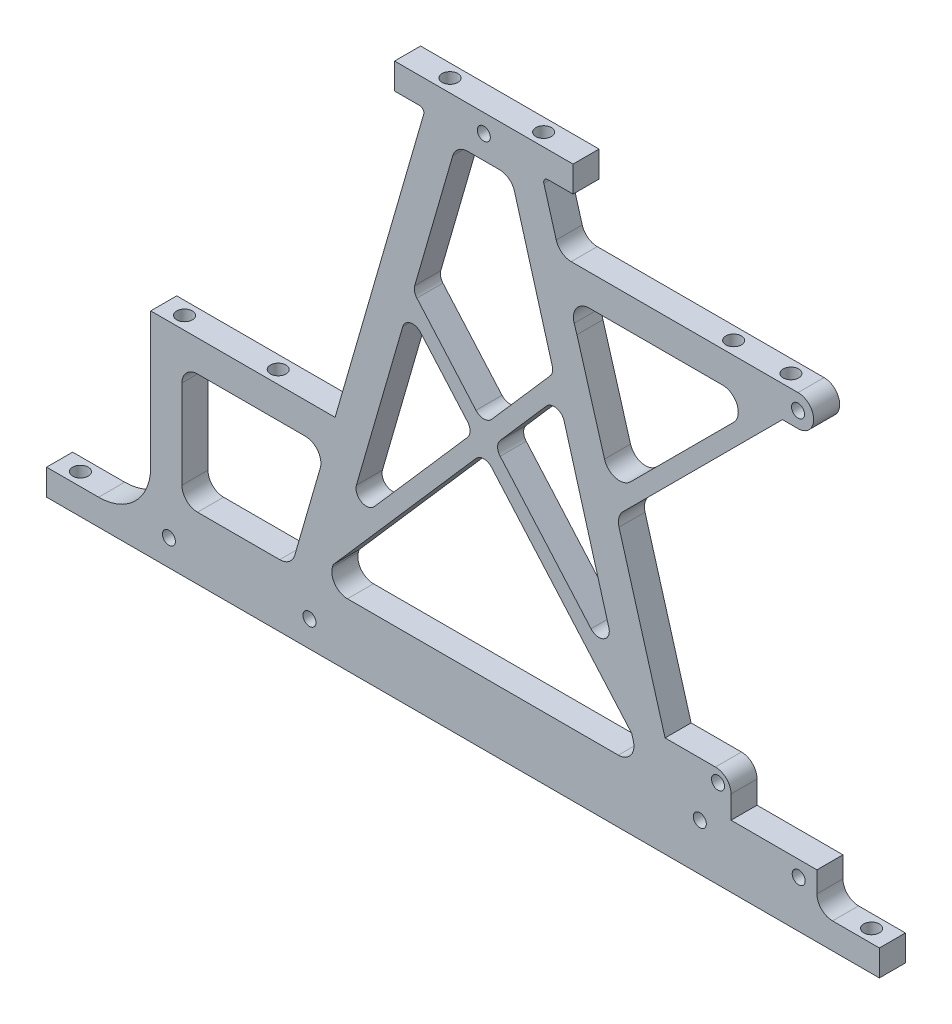
SolidWorks part; units mm, degrees
ref_plane "Front Plane" through (0, 0, 0) normal (0, 0, 1) x (1, 0, 0)
ref_plane "Top Plane" through (0, 0, 0) normal (0, 1, 0) x (1, 0, 0)
ref_plane "Right Plane" through (0, 0, 0) normal (1, 0, 0) x (0, 0, -1)
sketch "Sketch1" plane through (0, 0, 0) normal (0, 0, 1) x (1, 0, 0)
  line L0 (-84, 0) -> (0, 0)
  line L1 (0, 0) -> (76, 0)
  line L3 (-84, 0) -> (-84, 5)
  line L4 (76, 0) -> (76, 5)
  line L5 (-84, 5) -> (-74, 5)
  line L6 (-55, 35) -> (-34.2967, 35)
  line L7 (-58, 15) -> (-58, 32)
  line L8 (-64, 41) -> (-28.5744, 41)
  line L9 (101.5277, 0) -> (101.5277, 86) construction
  line L10 (-55, 12) -> (-39.2073, 12)
  line L11 (-64, 15) -> (-64, 41)
  line L13 (-26.1962, 12) -> (25.8389, 12)
  line L14 (15.4374, 62.3919) -> (24.03, 32.2749)
  line L18 (-29.0784, 15.8325) -> (-28.9404, 16.3102)
  line L19 (-36.3251, 14.1675) -> (-31.4145, 31.1675)
  line L20 (-28.5744, 41) -> (-11.5382, 99.978)
  line L21 (-3.1427, 53.0162) -> (-12.1526, 63.3245)
  line L24 (-17.1441, 106) -> (-17.1441, 101)
  line L25 (17.1441, 106) -> (17.1441, 101)
  line L26 (-27.957, 19.7146) -> (0, 51.7) construction
  line L27 (-28.9404, 16.3102) -> (-1.5059, 47.6979)
  line L28 (-21.0473, 29.8992) -> (-3.1427, 50.3838)
  line L29 (-24.4746, 31.7704) -> (-15.5799, 62.5633)
  line L31 (-29.0784, 15.8325) -> (-28.9404, 16.3102)
  line L32 (-13.2706, 70.5579) -> (-5.9699, 95.8325)
  line L33 (-17.1441, 101) -> (-12.3068, 101)
  line L34 (12.3068, 101) -> (17.1441, 101)
  line L35 (27.4471, 20.298) -> (0, 51.7) construction
  line L36 (20.6009, 30.41) -> (3.1427, 50.3838)
  line L37 (28.4125, 16.9142) -> (1.5059, 47.6979)
  line L39 (-24.4746, 31.7704) -> (-15.5799, 62.5633)
  line L40 (5.8993, 95.8231) -> (13.1495, 70.4109)
  line L41 (28.4125, 16.9142) -> (28.7238, 15.8231)
  line L42 (-5.4462, 45.4691) -> (13.9382, 67.6466) construction
  line L45 (3.615, 47.5641) -> (-14.0685, 67.7957) construction
  line L46 (-4.3168, 44.4819) -> (-1.5059, 47.6979)
  line L47 (4.7444, 48.5513) -> (3.1427, 50.3838)
  line L48 (-6.5756, 46.4562) -> (-3.1427, 50.3838)
  line L49 (2.4856, 46.577) -> (1.5059, 47.6979)
  line L50 (1.5059, 55.7021) -> (12.7321, 68.546)
  line L51 (-1.5059, 55.7021) -> (-12.8551, 68.6867)
  line L53 (3.1427, 53.0162) -> (12.0083, 63.1593)
  line L54 (34.8263, 19.356) -> (25.9751, 49.9985)
  line L55 (-17.1441, 106) -> (17.1441, 106)
  line L57 (60.3741, 89.5905) -> (16.7948, 89.5905)
  line L58 (60.3741, 83.5905) -> (57.3741, 83.5905)
  line L59 (13.9126, 91.758) -> (11.5382, 99.978)
  line L60 (17.8927, 77.9793) -> (17.3617, 79.6216)
  line L63 (26.7359, 52.9523) -> (57.3741, 83.5905)
  line L64 (28.1905, 58.6496) -> (48.0102, 78.4692)
  line L65 (17.8927, 77.9793) -> (23.1906, 59.9261)
  line L66 (45.8888, 83.5905) -> (20.2497, 83.5905)
  line L69 (3.0144, 98) -> (-3.0878, 98)
  line L70 (47.5, 12) -> (64, 12)
  line L73 (42.5844, 19.356) -> (34.8263, 19.356)
  line L76 (76, 5) -> (67, 5)
  line L78 (42.5844, 19.356) -> (44.5, 19.356)
  line L79 (47.5, 16.356) -> (47.5, 12)
  line L80 (64, 8) -> (64, 12)
  arc A0 (-74, 5) -> (-64, 15) centre (-74, 15) ccw
  arc A1 (-58, 32) -> (-55, 35) centre (-55, 32) cw
  arc A2 (-58, 15) -> (-55, 12) centre (-55, 15) ccw
  arc A4 (-36.3251, 14.1675) -> (-39.2073, 12) centre (-39.2073, 15) cw
  arc A5 (-34.2967, 35) -> (-31.4145, 31.1675) centre (-34.2967, 32) cw
  arc A6 (-26.1962, 12) -> (-29.0784, 15.8325) centre (-26.1962, 15) cw
  arc A7 (28.7238, 15.8231) -> (25.8389, 12) centre (25.8389, 15) cw
  arc A8 (-24.4746, 31.7704) -> (-21.0473, 29.8992) centre (-22.5532, 31.2154) ccw
  arc A9 (24.03, 32.2749) -> (20.6009, 30.41) centre (22.1067, 31.7262) cw
  arc A10 (1.5059, 47.6979) -> (-1.5059, 47.6979) centre (0, 46.3817) ccw
  arc A11 (-3.1427, 50.3838) -> (-3.1427, 53.0162) centre (-4.6485, 51.7) ccw
  arc A12 (3.1427, 50.3838) -> (3.1427, 53.0162) centre (4.6485, 51.7) cw
  arc A13 (1.5059, 55.7021) -> (-1.5059, 55.7021) centre (0, 57.0183) cw
  arc A14 (15.4374, 62.3919) -> (12.0083, 63.1593) centre (13.5142, 61.8431) ccw
  arc A15 (-15.5799, 62.5633) -> (-12.1526, 63.3245) centre (-13.6585, 62.0082) cw
  arc A16 (-13.2706, 70.5579) -> (-12.8551, 68.6867) centre (-11.3492, 70.0029) ccw
  arc A17 (12.7321, 68.546) -> (13.1495, 70.4109) centre (11.2263, 69.8622) ccw
  arc A18 (16.7948, 89.5905) -> (13.9126, 91.758) centre (16.7948, 92.5905) cw
  arc A19 (20.2497, 83.5905) -> (17.3617, 79.6216) centre (20.2497, 80.5553) ccw
  arc A20 (25.9751, 49.9985) -> (26.7359, 52.9523) centre (28.8573, 50.831) cw
  arc A21 (45.8888, 83.5905) -> (48.0102, 78.4692) centre (45.8888, 80.5905) cw
  arc A22 (23.1906, 59.9261) -> (28.1905, 58.6496) centre (26.0692, 60.7709) ccw
  arc A23 (60.3741, 83.5905) -> (60.3741, 89.5905) centre (60.3741, 86.5905) ccw
  circle A24 centre (0, 102.5) radius 1.25
  arc A25 (5.8993, 95.8231) -> (3.0144, 98) centre (3.0144, 95) ccw
  arc A26 (-5.9699, 95.8325) -> (-3.0878, 98) centre (-3.0878, 95) cw
  arc A27 (47.5, 16.356) -> (44.5, 19.356) centre (44.5, 16.356) ccw
  circle A28 centre (45, 17) radius 1.25
  arc A29 (67, 5) -> (64, 8) centre (67, 8) cw
  circle A30 centre (41.5, 9) radius 1.25
  circle A31 centre (60.5, 9) radius 1.25
  circle A32 centre (60.3741, 86.5905) radius 1.25
  arc A33 (12.3068, 101) -> (11.5382, 99.978) centre (12.3068, 100.2) ccw
  arc A34 (-12.3068, 101) -> (-11.5382, 99.978) centre (-12.3068, 100.2) cw
  point P15 (-64, 10.7499)
  point P16 (-64, 12)
  point P37 (29.8146, 12)
  point P38 (-34.7, 12)
  point P42 (-33.5706, 11.0128)
  point P43 (1.1294, 50.7128)
  point P44 (-35.8294, 12.9872)
  point P45 (-1.1294, 52.6872)
  point P51 (-26.9737, 23.1189)
  point P52 (35.8294, 12.9872)
  point P54 (34.7, 12)
  point P55 (1.1294, 52.6872)
  point P56 (33.5706, 11.0128)
  point P57 (-1.1294, 50.7128)
  point P71 (23.2361, 76.005)
  point P73 (-18.0243, 74.6008)
  point P75 (20.9774, 77.9793)
  point P84 (1.1294, 52.6872)
  point P85 (35.8294, 12.9872)
  point P92 (0, 53.9793)
  point P98 (-13.5737, 69.5088)
  point P101 (13.4479, 69.365)
  point P103 (0, 109.9718)
  point P110 (131.4017, 89.5905)
  point P115 (14.5387, 89.5905)
  point P124 (0, 51.7)
  point P128 (24.6146, 55.0737)
  point P129 (55.2528, 85.7118)
  point P133 (53.1315, 83.5905)
  point P147 (0, 98)
extrude "Boss-Extrude1" add sketch "Sketch1" along normal blind 5 contours L33 A34 L20 L8 L11 A0 L5 L3 L0 L1 L4 L76 A29 L80 L70 L79 A27 L78 L73 L54 A20 L63 L58 A23 L57 A18 L59 A33 L34 L25 L55 L24 L32 A26 L69 A25 L40 A17 L50 A13 L51 A16 L29 A15 L21 A11 L28 A8
sketch "Sketch2" plane through (0, 0, 5) normal (0, 0, 1) x (1, 0, 0)
  line L0 (0, 0) -> (0, 73.8488) construction
  line L1 (0, 0) -> (0, -16.6265) construction
  line L2 (0, -16.6265) -> (-33.5, -16.6265) construction
  circle A0 centre (-33.5, 5) radius 1.25
  circle A1 centre (-60.5, 5) radius 1.25
  dimension "D1" = 33.5
extrude "Cut-Extrude1" cut sketch "Sketch2" against normal blind 15
sketch "Sketch3" plane through (0, 106, 0) normal (0, 1, 0) x (1, 0, 0)
  line L0 (0, 0) -> (0, 9.6733) construction
  line L1 (0, 9.6733) -> (-80, 9.6733) construction
  line L2 (0, -5) -> (0, -2.5) construction
  line L3 (-17.1441, -5) -> (17.1441, -5) construction
  line L4 (87.9394, -2.5) -> (-87.9394, -2.5) construction
  line L5 (-80, 9.6733) -> (-80, -2.5) construction
  circle A0 centre (-80, -2.5) radius 1.5
  point P11 (0, -2.5)
  dimension "D1" = 80
  dimension "D2" = 2.5
extrude "Cut-Extrude2" cut sketch "Sketch3" against normal blind 115
sketch "Sketch4" plane through (0, 106, 0) normal (0, 1, 0) x (1, 0, 0)
  line L0 (-80, -2.5) -> (-80, 9.4148) construction
  line L1 (-80, 9.4148) -> (45.5, 9.4148) construction
  line L2 (45.5, 9.4148) -> (45.5, -2.5) construction
  circle A0 centre (45.5, -2.5) radius 1.5
  circle A1 centre (56.5, -2.5) radius 1.5
  dimension "D1" = 125.5
extrude "Cut-Extrude3" cut sketch "Sketch4" against normal blind 25
sketch "Sketch5" plane through (0, 106, 0) normal (0, 1, 0) x (1, 0, 0)
  line L0 (0, 0) -> (0, 15.7487) construction
  line L1 (0, 15.7487) -> (72, 15.7487) construction
  line L2 (72, 15.7487) -> (72, -2.5) construction
  line L3 (76, -2.5) -> (68.2114, -2.5) construction
  line L4 (76, -5) -> (76, 0) construction
  circle A0 centre (72, -2.5) radius 1.5
  dimension "D1" = 72
extrude "Cut-Extrude4" cut sketch "Sketch5" against normal blind 115
sketch "Sketch6" plane through (0, 106, 0) normal (0, 1, 0) x (1, 0, 0)
  line L0 (0, 0) -> (0, -2.5) construction
  line L1 (0, -2.5) -> (-42, -2.5) construction
  circle A0 centre (-42, -2.5) radius 1.5
  circle A1 centre (-60, -2.5) radius 1.5
extrude "Cut-Extrude5" cut sketch "Sketch6" against normal blind 76
sketch "Sketch8" plane through (0, 106, 0) normal (0, 1, 0) x (1, 0, 0)
  line L0 (0, 0) -> (0, -2.5) construction
  line L1 (0, -2.5) -> (-9, -2.5) construction
  circle A0 centre (-9, -2.5) radius 1.5
  circle A1 centre (9, -2.5) radius 1.5
extrude "Cut-Extrude6" cut sketch "Sketch8" against normal blind 11
